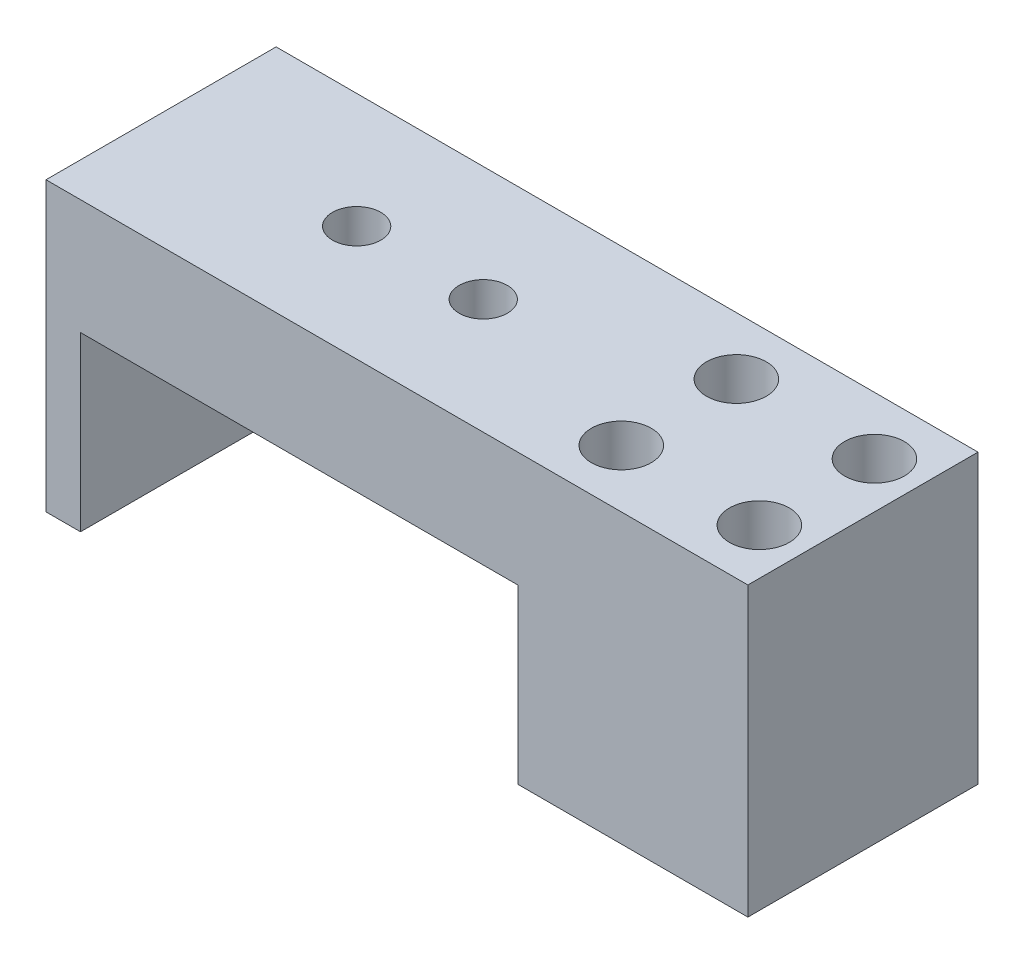
SolidWorks part; units mm, degrees
ref_plane "前视基准面" through (0, 0, 0) normal (0, 0, 1) x (1, 0, 0)
ref_plane "上视基准面" through (0, 0, 0) normal (0, 1, 0) x (1, 0, 0)
ref_plane "右视基准面" through (0, 0, 0) normal (1, 0, 0) x (0, 0, -1)
sketch "草图1" plane through (0, 0, 0) normal (0, 1, 0) x (1, 0, 0)
  line L1 (-6, -5) -> (6, -5) construction
  line L2 (-6, -5) -> (-6, 5) construction
  line L3 (-6, 5) -> (6, 5) construction
  line L4 (6, -5) -> (6, 5) construction
  line L5 (0, 5) -> (0, -5) construction
  line L6 (-6, 0) -> (6, 0) construction
  line L7 (-10, -10) -> (10, -10)
  line L8 (-10, -10) -> (-10, 10)
  line L9 (-10, 10) -> (10, 10)
  line L10 (10, -10) -> (10, 10)
  line L11 (0, 10) -> (0, -10) construction
  line L12 (-10, 0) -> (10, 0) construction
  circle A0 centre (-6, 5) radius 2.6
  circle A1 centre (6, 5) radius 2.6
  circle A2 centre (-6, -5) radius 2.6
  circle A3 centre (6, -5) radius 2.6
  point P0 (0, 0)
  point P8 (0, 0)
  dimension "D3" = 5.2
  dimension "D1" = 10
  dimension "D2" = 12
  dimension "D4" = 20
  dimension "D5" = 20
extrude "凸台-拉伸1" add sketch "草图1" along normal blind 25
sketch "草图2" plane through (0, 25, 0) normal (0, 1, 0) x (1, 0, 0)
  line L0 (-10, -10) -> (10, -10) construction
  line L1 (10, 10) -> (-51, 10)
  line L2 (10, 10) -> (10, -10)
  line L3 (10, -10) -> (-51, -10)
  line L4 (-51, 10) -> (-51, -10)
  line L5 (-10, 10) -> (-10, -10) construction
  line L6 (-10, 10) -> (-10, -10)
  line M7 (-10, 10) -> (-10, -10)
  dimension "D1" = 41
extrude "凸台-拉伸2" add sketch "草图2" against normal blind 10 contours L1 L4 L3 M7
sketch "草图3" plane through (0, 15, 0) normal (0, -1, 0) x (1, 0, 0)
  line L0 (-10, -10) -> (-51, -10) construction
  line L1 (-51, 10) -> (-48, 10)
  line L2 (-51, 10) -> (-51, -10)
  line L3 (-51, -10) -> (-48, -10)
  line L4 (-48, 10) -> (-48, -10)
  dimension "D1" = 3
extrude "凸台-拉伸3" add sketch "草图3" along normal blind 15
sketch "草图4" plane through (0, 25, 0) normal (0, 1, 0) x (1, 0, 0)
  line L0 (-48, 0) -> (-10, 0) construction
  line L3 (-29, 0) -> (-29, 10) construction
  line L7 (-48, 10) -> (-48, -10)
  line L8 (-10, 10) -> (-48, 10)
  line L9 (-10, -10) -> (-10, 10)
  line L10 (-48, -10) -> (-10, -10)
  line L11 (-48, 10) -> (-48, -10) construction
  line L12 (-10, 10) -> (-48, 10) construction
  line L13 (-10, -10) -> (-10, 10) construction
  line L14 (-48, -10) -> (-10, -10) construction
  circle A0 centre (-34, 0) radius 2.1
  circle A1 centre (-23, 0) radius 2.1
  dimension "D2" = 5
  dimension "D3" = 4.2
  dimension "D4" = 4.2
  dimension "D5" = 6
  dimension "D1" = 0
extrude "切除-拉伸1" cut sketch "草图4" against normal through all
